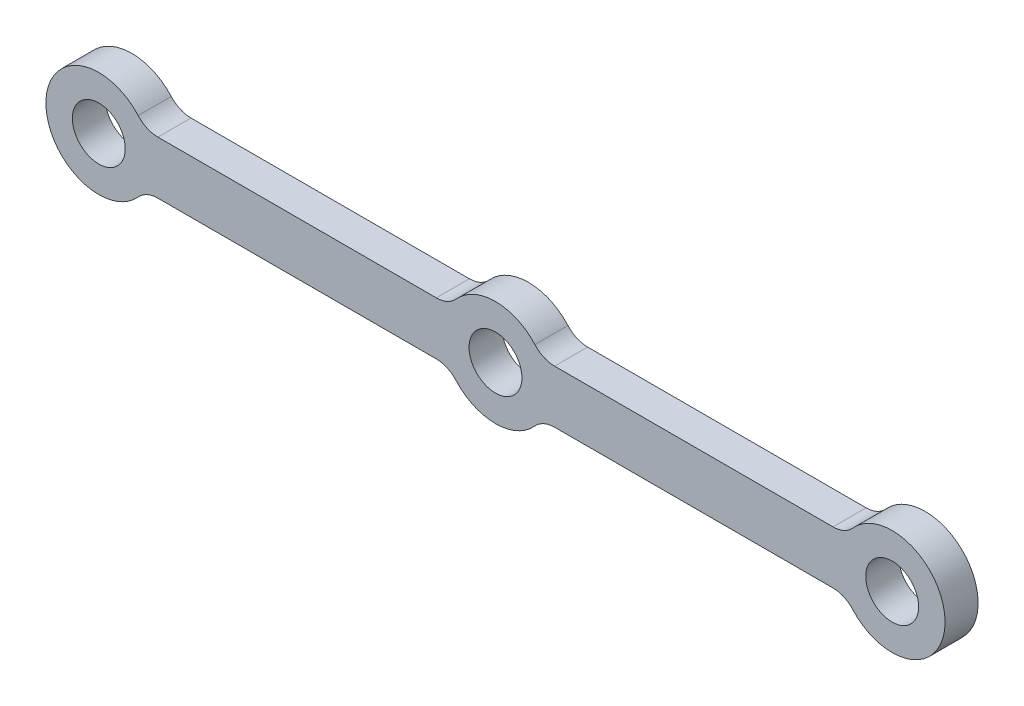
SolidWorks part; units mm, degrees
material "Acrylic (Medium-high impact)"
ref_plane "Front Plane" through (0, 0, 0) normal (0, 0, 1) x (1, 0, 0)
ref_plane "Top Plane" through (0, 0, 0) normal (0, 1, 0) x (1, 0, 0)
ref_plane "Right Plane" through (0, 0, 0) normal (1, 0, 0) x (0, 0, -1)
sketch "Sketch1" plane through (0, 0, 0) normal (0, 0, 1) x (1, 0, 0)
  line L0 (0, 5.08) -> (0, 0) construction
  line L1 (0, 0) -> (76.2, 0)
  line L2 (0, 0) -> (0, 5.08)
  line L3 (0, 5.08) -> (76.2, 5.08)
  line L4 (76.2, 0) -> (76.2, 5.08)
  line L5 (0, 2.54) -> (76.2, 2.54) construction
  line L6 (0, 5.08) -> (76.2, 5.08) construction
  line L7 (38.1, 5.08) -> (38.1, 0) construction
  circle A0 centre (0, 2.54) radius 5.08
  circle A1 centre (76.2, 2.54) radius 5.08
  circle A2 centre (38.1, 2.54) radius 5.08
  dimension "D3" = 10.16
  dimension "D4" = 10.16
  dimension "D5" = 10.16
  dimension "D1" = 76.2
  dimension "D2" = 5.08
extrude "Boss-Extrude1" add sketch "Sketch1" along normal blind 3.175 contours L3 A0 L1 L2 | L1 A0 L3 L2 | A2 L3 A0 L1 | L3 A2 L1 | L3 A2 | A2 L1 A1 L3 | L1 A1 L3 L4 | L3 A1 L1 L4
sketch "Sketch2" plane through (0, 0, 3.175) normal (0, 0, 1) x (1, 0, 0)
  line L0 (-5.08, 2.54) -> (81.28, 2.54) construction
  line L1 (76.2, 7.62) -> (76.2, -2.54) construction
  line L2 (38.1, 7.62) -> (38.1, -2.54) construction
  line L3 (0, 7.62) -> (0, -2.54) construction
  arc A0 (4.3994, 5.08) -> (4.3994, 0) centre (0, 2.54) ccw construction
  arc A1 (71.8006, 0) -> (71.8006, 5.08) centre (76.2, 2.54) ccw construction
  arc A2 (42.4994, 5.08) -> (33.7006, 5.08) centre (38.1, 2.54) ccw construction
  arc A3 (33.7006, 0) -> (42.4994, 0) centre (38.1, 2.54) ccw construction
  circle A4 centre (0, 2.54) radius 2.54
  circle A5 centre (76.2, 2.54) radius 2.54
  circle A6 centre (38.1, 2.54) radius 2.54
  dimension "D1" = 5.08
  dimension "D2" = 5.08
  dimension "D3" = 5.08
extrude "Cut-Extrude1" cut sketch "Sketch2" against normal through all both and the other way through all
fillet "Fillet1" radius 2.54 8 edges at (4.3994, 0, 1.5875) (42.4994, 0, 1.5875) (33.7006, 0, 1.5875) (71.8006, 0, 1.5875) (71.8006, 5.08, 1.5875) (33.7006, 5.08, 1.5875) (42.4994, 5.08, 1.5875) (4.3994, 5.08, 1.5875)
equation "\"hole-size\"= 0.2"
equation "\"D1@Sketch2\"=\"hole-size\""
equation "\"D3@Sketch2\"=\"hole-size\""
equation "\"D2@Sketch2\"=\"hole-size\""
